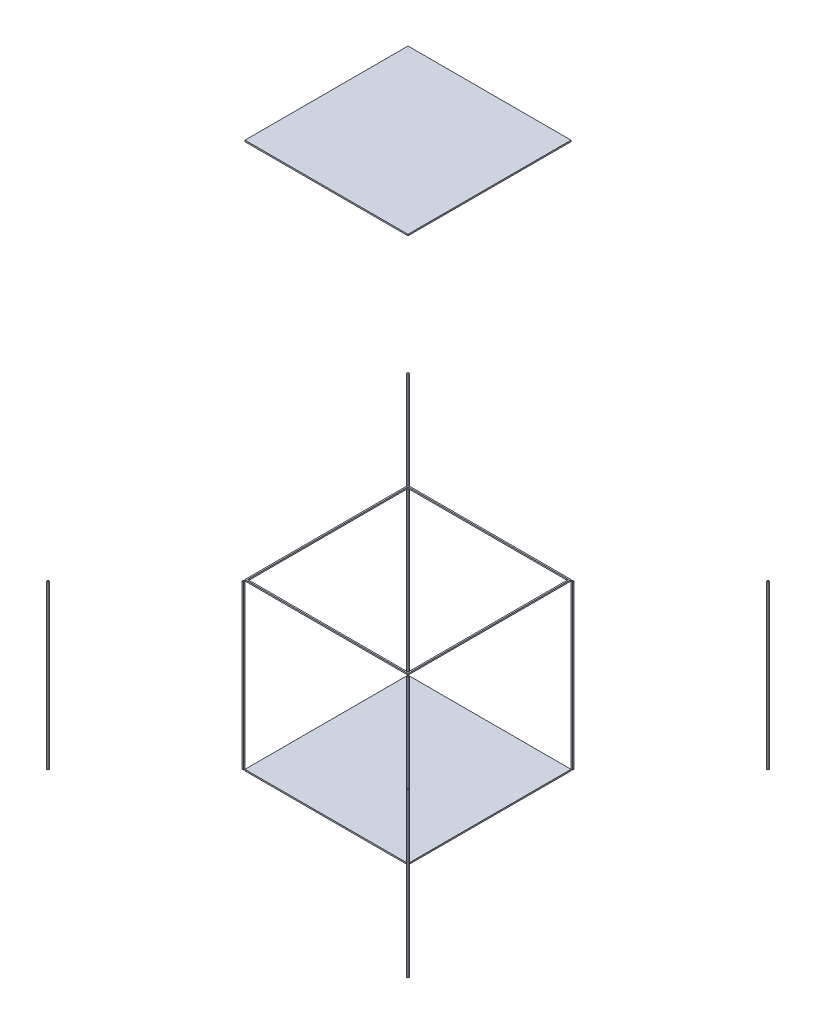
SolidWorks part; units mm, degrees
ref_plane "Front Plane" through (0, 0, 0) normal (0, 0, 1) x (1, 0, 0)
ref_plane "Top Plane" through (0, 0, 0) normal (0, 1, 0) x (1, 0, 0)
ref_plane "Right Plane" through (0, 0, 0) normal (1, 0, 0) x (0, 0, -1)
sketch "Sketch1" plane through (0, 0, 0) normal (0, 1, 0) x (1, 0, 0)
  line L1 (190.5, 190.5) -> (-190.5, 190.5)
  line L2 (190.5, 190.5) -> (190.5, -190.5)
  line L3 (190.5, -190.5) -> (-190.5, -190.5)
  line L4 (-190.5, 190.5) -> (-190.5, -190.5)
  line L5 (190.5, 190.5) -> (-190.5, -190.5) construction
  line L6 (190.5, -190.5) -> (-190.5, 190.5) construction
  point P0 (0, 0)
  dimension "D1" = 381
  dimension "D2" = 381
extrude "Boss-Extrude1" add sketch "Sketch1" along normal blind 3.175
sketch "Sketch3" plane through (0, 3.175, 0) normal (0, 1, 0) x (1, 0, 0)
  line L1 (190.5, 190.5) -> (193.675, 190.5)
  line L2 (190.5, 190.5) -> (190.5, 193.675)
  line L3 (190.5, 193.675) -> (193.675, 193.675)
  line L4 (193.675, 190.5) -> (193.675, 193.675)
  line L5 (190.5, -190.5) -> (193.675, -190.5)
  line L6 (190.5, -190.5) -> (190.5, -193.675)
  line L7 (190.5, -193.675) -> (193.675, -193.675)
  line L8 (193.675, -190.5) -> (193.675, -193.675)
  line L9 (-190.5, -190.5) -> (-193.675, -190.5)
  line L10 (-190.5, -190.5) -> (-190.5, -193.675)
  line L11 (-190.5, -193.675) -> (-193.675, -193.675)
  line L12 (-193.675, -190.5) -> (-193.675, -193.675)
  line L13 (-190.5, 190.5) -> (-193.675, 190.5)
  line L14 (-190.5, 190.5) -> (-190.5, 193.675)
  line L15 (-190.5, 193.675) -> (-193.675, 193.675)
  line L16 (-193.675, 190.5) -> (-193.675, 193.675)
  dimension "D1" = 3.175
extrude "Boss-Extrude2" add sketch "Sketch3" along normal blind 381 separate body
sketch "Sketch4" plane through (0, 384.175, 0) normal (0, 1, 0) x (1, 0, 0)
  line L1 (190.5, -190.5) -> (-190.5, -190.5)
  line L2 (190.5, -190.5) -> (190.5, 190.5)
  line L3 (190.5, 190.5) -> (-190.5, 190.5)
  line L4 (-190.5, -190.5) -> (-190.5, 190.5)
  line L5 (190.5, -190.5) -> (-190.5, 190.5) construction
  line L6 (190.5, 190.5) -> (-190.5, -190.5) construction
  line L7 (187.325, -187.325) -> (-187.325, -187.325)
  line L8 (187.325, -187.325) -> (187.325, 187.325)
  line L9 (187.325, 187.325) -> (-187.325, 187.325)
  line L10 (-187.325, -187.325) -> (-187.325, 187.325)
  line L11 (187.325, -187.325) -> (-187.325, 187.325) construction
  line L12 (187.325, 187.325) -> (-187.325, -187.325) construction
  point P0 (0, 0)
  point P7 (0, 0)
  dimension "D1" = 374.65
extrude "Boss-Extrude3" add sketch "Sketch4" along normal blind 3.175 separate body
sketch "Sketch5" plane through (0, 3.175, 0) normal (0, 1, 0) x (1, 0, 0)
  line L1 (-422.275, -422.275) -> (-419.1, -422.275)
  line L2 (-422.275, -422.275) -> (-422.275, -419.1)
  line L3 (-422.275, -419.1) -> (-419.1, -419.1)
  line L4 (-419.1, -422.275) -> (-419.1, -419.1)
  line L5 (-422.275, -422.275) -> (-419.1, -419.1) construction
  line L6 (-422.275, -419.1) -> (-419.1, -422.275) construction
  line L7 (-422.275, 422.275) -> (-419.1, 422.275)
  line L8 (-422.275, 422.275) -> (-422.275, 419.1)
  line L9 (-422.275, 419.1) -> (-419.1, 419.1)
  line L10 (-419.1, 422.275) -> (-419.1, 419.1)
  line L11 (-422.275, 422.275) -> (-419.1, 419.1) construction
  line L12 (-422.275, 419.1) -> (-419.1, 422.275) construction
  line L13 (422.275, 422.275) -> (419.1, 422.275)
  line L14 (422.275, 422.275) -> (422.275, 419.1)
  line L15 (422.275, 419.1) -> (419.1, 419.1)
  line L16 (419.1, 422.275) -> (419.1, 419.1)
  line L17 (422.275, 422.275) -> (419.1, 419.1) construction
  line L18 (422.275, 419.1) -> (419.1, 422.275) construction
  line L19 (422.275, -422.275) -> (419.1, -422.275)
  line L20 (422.275, -422.275) -> (422.275, -419.1)
  line L21 (422.275, -419.1) -> (419.1, -419.1)
  line L22 (419.1, -422.275) -> (419.1, -419.1)
  line L23 (422.275, -422.275) -> (419.1, -419.1) construction
  line L24 (422.275, -419.1) -> (419.1, -422.275) construction
  line L25 (420.6875, -420.6875) -> (-420.6875, -420.6875) construction
  line L26 (420.6875, -420.6875) -> (420.6875, 420.6875) construction
  line L27 (420.6875, 420.6875) -> (-420.6875, 420.6875) construction
  line L28 (-420.6875, -420.6875) -> (-420.6875, 420.6875) construction
  line L29 (420.6875, -420.6875) -> (-420.6875, 420.6875) construction
  line L30 (420.6875, 420.6875) -> (-420.6875, -420.6875) construction
  point P0 (-420.6875, -420.6875)
  point P5 (-420.6875, 420.6875)
  point P10 (420.6875, 420.6875)
  point P15 (420.6875, -420.6875)
  point P20 (0, 0)
  point P26 (0, 0)
  point P27 (0, 0)
  point P28 (0, 0)
  point P29 (0, 0)
  dimension "D1" = 3.175
  dimension "D2" = 841.375
extrude "Boss-Extrude4" add sketch "Sketch5" along normal blind 381 separate body
ref_plane "Plane1" through (0, 1273.175, 0) normal (0, 1, 0) x (1, 0, 0)
sketch "Sketch6" plane through (0, 1273.175, 0) normal (0, 1, 0) x (1, 0, 0)
  line L1 (190.5, -190.5) -> (-190.5, -190.5)
  line L2 (190.5, -190.5) -> (190.5, 190.5)
  line L3 (190.5, 190.5) -> (-190.5, 190.5)
  line L4 (-190.5, -190.5) -> (-190.5, 190.5)
  line L5 (190.5, -190.5) -> (-190.5, 190.5) construction
  line L6 (190.5, 190.5) -> (-190.5, -190.5) construction
  point P0 (0, 0)
extrude "Boss-Extrude5" add sketch "Sketch6" along normal blind 3.175 separate body
